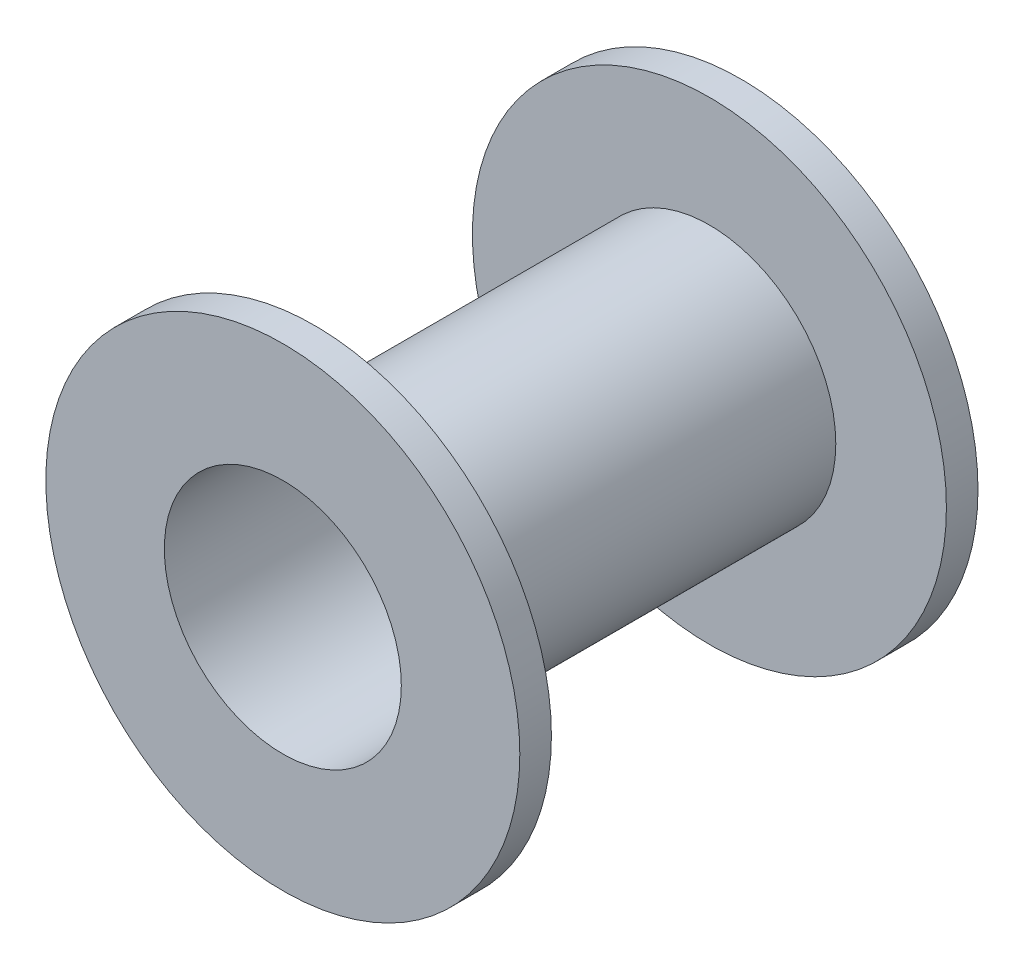
SolidWorks part; units mm, degrees
ref_plane "Front Plane" through (0, 0, 0) normal (0, 0, 1) x (1, 0, 0)
ref_plane "Top Plane" through (0, 0, 0) normal (0, 1, 0) x (1, 0, 0)
ref_plane "Right Plane" through (0, 0, 0) normal (1, 0, 0) x (0, 0, -1)
sketch "Sketch1" plane through (0, 0, 0) normal (0, 0, 1) x (1, 0, 0)
  circle A0 centre (0, 0) radius 15
  circle A1 centre (0, 0) radius 16
  dimension "D1" = 30
  dimension "D2" = 32
extrude "Boss-Extrude1" add sketch "Sketch1" along normal blind 50
ref_plane "Plane1" through (0, 0, 25) normal (0, 0, -1) x (-1, 0, 0)
sketch "Sketch2" plane through (0, 0, 50) normal (0, 0, 1) x (1, 0, 0)
  circle A0 centre (0, 0) radius 15 construction
  circle A1 centre (0, 0) radius 15
  circle A2 centre (0, 0) radius 30
  dimension "D1" = 15
extrude "Boss-Extrude2" add sketch "Sketch2" along normal blind 4
mirror "Mirror1" about plane through (0, 0, 25) normal (0, 0, -1) of "Boss-Extrude2"
